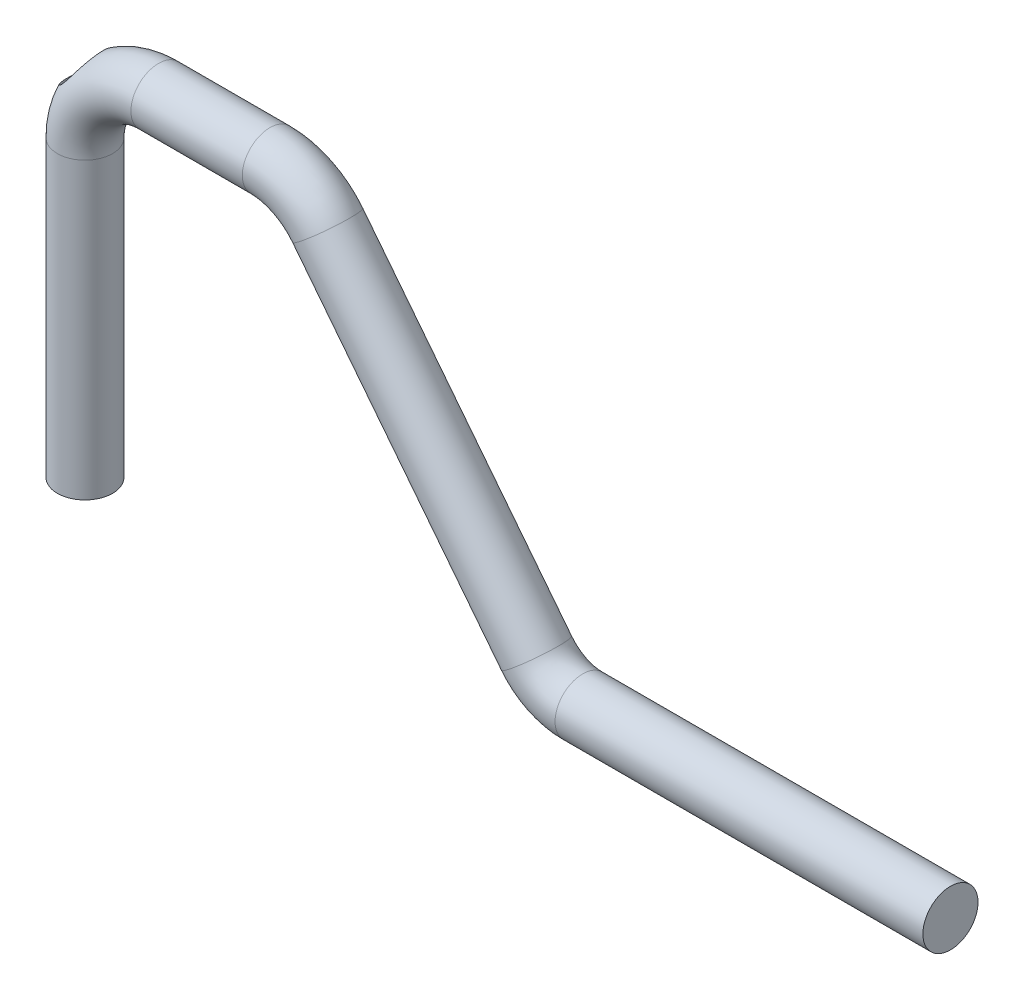
SolidWorks part; units mm, degrees
material "6061 Alloy"
ref_plane "Front Plane" through (0, 0, 0) normal (0, 0, 1) x (1, 0, 0)
ref_plane "Top Plane" through (0, 0, 0) normal (0, 1, 0) x (1, 0, 0)
ref_plane "Right Plane" through (0, 0, 0) normal (1, 0, 0) x (0, 0, -1)
sketch "Sketch1" plane through (0, 0, 0) normal (0, 0, 1) x (1, 0, 0)
  line L0 (0, 0) -> (0, 101.6)
  line L1 (25.4, 127) -> (63.8459, 127)
  line L2 (83.8272, 117.2815) -> (155.9367, 25.4)
  line L3 (171.8399, 17.665) -> (298.8399, 17.665)
  arc A0 (25.4, 127) -> (0, 101.6) centre (25.4, 101.6) ccw
  arc A1 (83.8272, 117.2815) -> (63.8459, 127) centre (63.8459, 101.6) ccw
  arc A2 (155.9367, 25.4) -> (171.8399, 17.665) centre (171.8399, 37.8809) ccw
  point P9 (0, 127)
  point P12 (76.2, 127)
  dimension "D3" = 25.4
  dimension "D5" = 127
  dimension "D1" = 127
  dimension "D2" = 76.2
  dimension "D4" = 101.6
sketch "Sketch2" plane through (0, 0, 0) normal (0, 1, 0) x (1, 0, 0)
  circle A0 centre (0, 0) radius 9.525
  dimension "D1" = 19.05
sweep "Sweep1" add profiles "Sketch2" path "Sketch1"
sketch "Sketch6" plane through (0, 0, 0) normal (0, -1, 0) x (1, 0, 0)
  circle A0 centre (0, 0) radius 6.35
  dimension "D1" = 12.7
extrude "Cut-Extrude1" cut sketch "Sketch6" against normal blind 139.7
